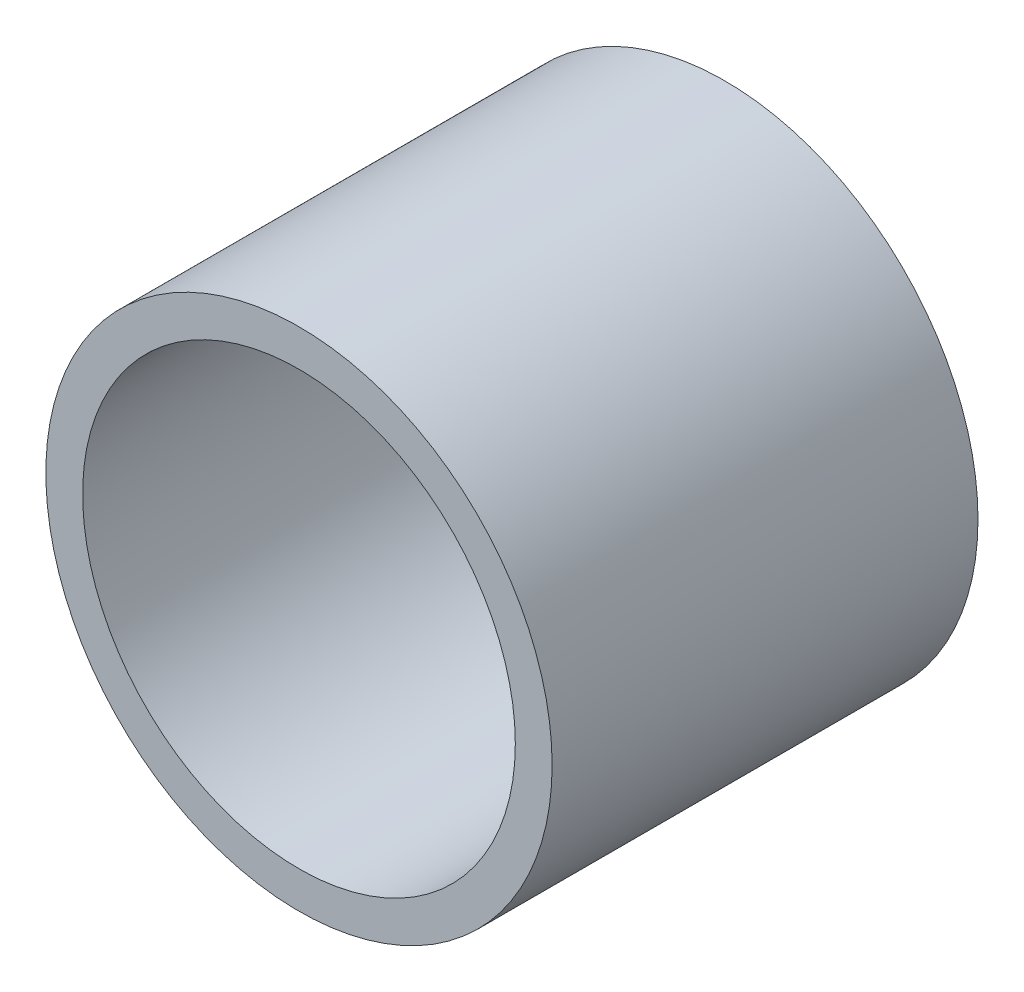
SolidWorks part; units mm, degrees
ref_plane "Alzado" through (0, 0, 0) normal (0, 0, 1) x (1, 0, 0)
ref_plane "Planta" through (0, 0, 0) normal (0, 1, 0) x (1, 0, 0)
ref_plane "Vista lateral" through (0, 0, 0) normal (1, 0, 0) x (0, 0, -1)
sketch "Croquis1" plane through (0, 0, 0) normal (0, 0, 1) x (1, 0, 0)
  circle A0 centre (0, 0) radius 25.4
  circle A1 centre (0, 0) radius 29.72
  dimension "D1" = 59.44
  dimension "D2" = 50.8
extrude "Saliente-Extruir1" add sketch "Croquis1" along normal blind 50
